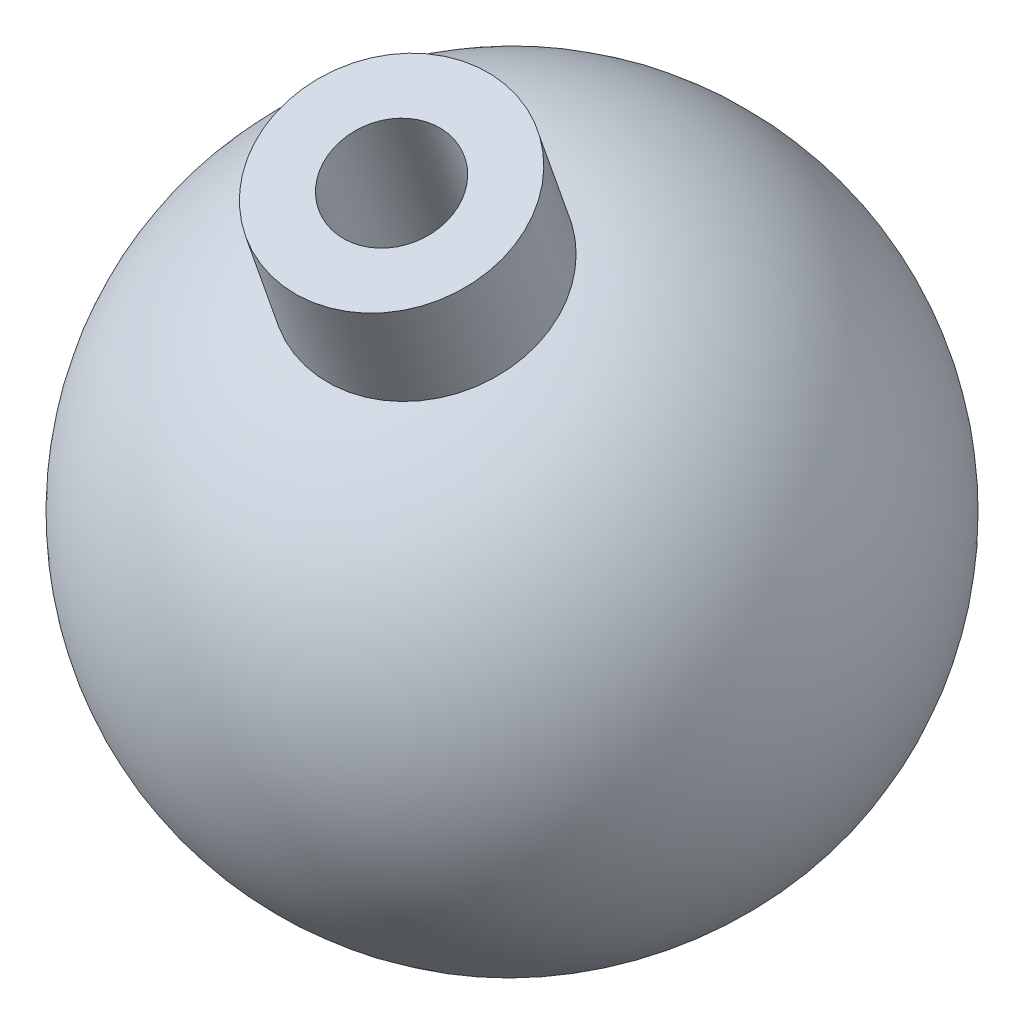
SolidWorks part; units mm, degrees
other "Cable End Ball Socket"
ref_plane "Front Plane" through (0, 0, 0) normal (0, 0, 1) x (1, 0, 0)
ref_plane "Top Plane" through (0, 0, 0) normal (0, 1, 0) x (1, 0, 0)
ref_plane "Right Plane" through (0, 0, 0) normal (1, 0, 0) x (0, 0, -1)
sketch3d "Turned socket body axis line"
  line L0 (-24.4208, -99.1604, -22.8742) -> (-22.3446, -80.8396, -15.1258) construction
ref_axis "Turned socket body axis" through (-24.4208, -99.1604, -22.8742) along (0.1038, 0.916, 0.3874)
sketch3d "Ball socket turned profile datum points"
  point P0 (-23.3827, -90, -19)
  point P1 (-22.3446, -80.8396, -15.1258)
  point P2 (-13.4367, -90.9561, -19.4044)
ref_plane "Ball socket turned profile plane" through (0, -6.8394, 16.1713) normal (0, 0.3895, -0.921) x (-1, 0, 0)
sketch "Ball socket turned profile" plane through (0, -6.8394, 16.1713) normal (0, 0.3895, -0.921) x (-1, 0, 0)
  line L0 (21.4504, -86.2284) -> (21.2887, -84.6794)
  line L1 (21.2887, -84.6794) -> (22.0346, -84.6016)
  line L2 (22.0346, -84.6016) -> (22.2838, -86.9886)
  line L3 (22.2838, -86.9886) -> (23.0297, -86.9107)
  line L4 (23.0297, -86.9107) -> (23.0609, -87.2091)
  line L5 (20.7241, -91.8867) -> (19.8043, -93.0209)
  arc A0 (21.4504, -86.2284) -> (19.8043, -93.0209) centre (23.3827, -90.2924) ccw
  arc A1 (23.0609, -87.2091) -> (20.7241, -91.8867) centre (23.3827, -90.2924) ccw
revolve "Turned socket body" add sketch "Ball socket turned profile" angle 360 about axis through (-24.4208, -99.1604, -22.8742) along (0.1038, 0.916, 0.3874)
